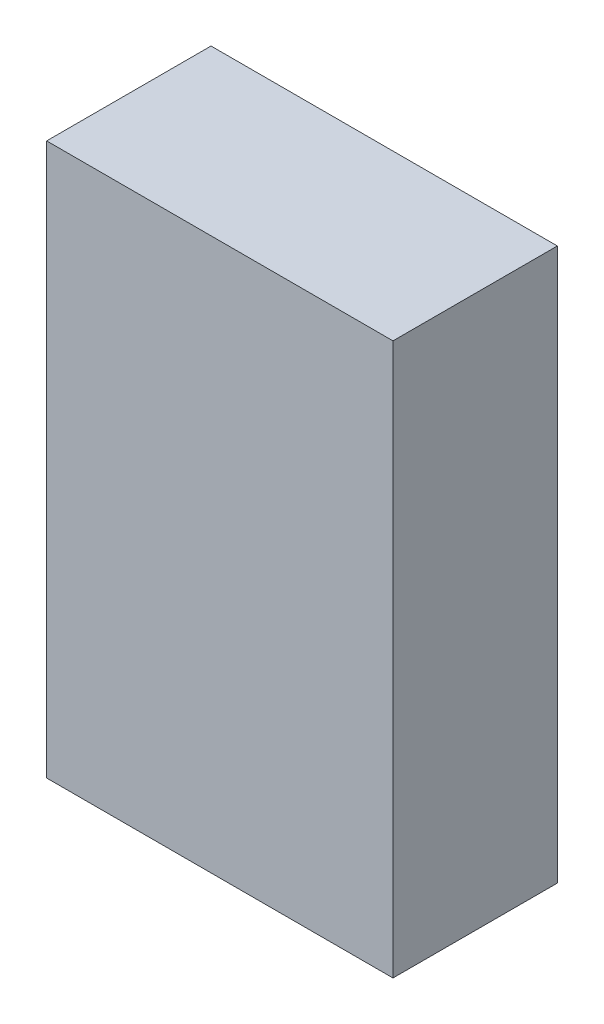
SolidWorks part; units mm, degrees
ref_plane "Front Plane" through (0, 0, 0) normal (0, 0, 1) x (1, 0, 0)
ref_plane "Top Plane" through (0, 0, 0) normal (0, 1, 0) x (1, 0, 0)
ref_plane "Right Plane" through (0, 0, 0) normal (1, 0, 0) x (0, 0, -1)
sketch "Sketch1" plane through (0, 0, 0) normal (0, 0, 1) x (1, 0, 0)
  line L0 (63.4055, -109.39) -> (123.797, -109.39) construction
  line L1 (53.4055, -19.39) -> (108.4055, -19.39)
  line L2 (53.4055, -19.39) -> (53.4055, -109.39)
  line L3 (53.4055, -109.39) -> (108.4055, -109.39)
  line L4 (108.4055, -19.39) -> (108.4055, -109.39)
  line L5 (108.4055, -99.39) -> (108.4055, -29.39) construction
  line L6 (53.4055, -29.39) -> (53.4055, -59.39) construction
  line L7 (73.4055, -19.39) -> (63.4055, -19.39) construction
extrude "Extrude-Thin1" add sketch "Sketch1" along normal blind 26 thin thin type one direction wall 2
sketch "Sketch2" plane through (0, 0, 26) normal (0, 0, 1) x (1, 0, 0)
  line L4 (51.4055, -17.39) -> (51.4055, -111.39)
  line L5 (51.4055, -111.39) -> (110.4055, -111.39)
  line L6 (110.4055, -111.39) -> (110.4055, -17.39)
  line L7 (110.4055, -17.39) -> (51.4055, -17.39)
  line L8 (51.4055, -17.39) -> (51.4055, -111.39)
  line L9 (51.4055, -111.39) -> (110.4055, -111.39)
  line L10 (110.4055, -111.39) -> (110.4055, -17.39)
  line L11 (110.4055, -17.39) -> (51.4055, -17.39)
  dimension "D1" = 0
extrude "Boss-Extrude1" add sketch "Sketch2" along normal blind 2
